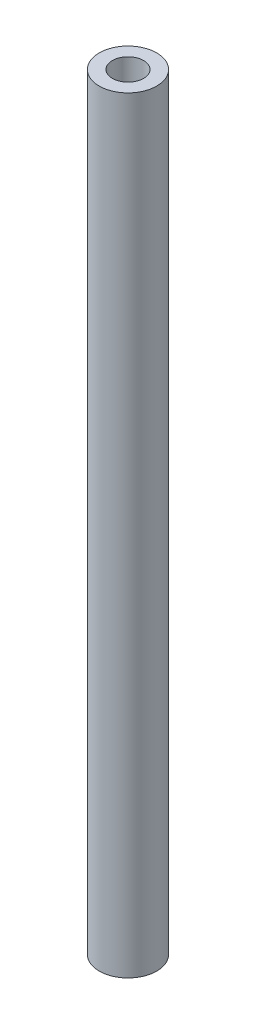
SolidWorks part; units mm, degrees
ref_plane "Front Plane" through (0, 0, 0) normal (0, 0, 1) x (1, 0, 0)
ref_plane "Top Plane" through (0, 0, 0) normal (0, 1, 0) x (1, 0, 0)
ref_plane "Right Plane" through (0, 0, 0) normal (1, 0, 0) x (0, 0, -1)
sketch "Sketch1" plane through (0, 0, 0) normal (0, 1, 0) x (1, 0, 0)
  circle A0 centre (0, 0) radius 4.1275
  circle A1 centre (0, 0) radius 7.62
  dimension "D1" = 8.255
  dimension "D2" = 15.24
extrude "Boss-Extrude1" add sketch "Sketch1" along normal blind 203.2
